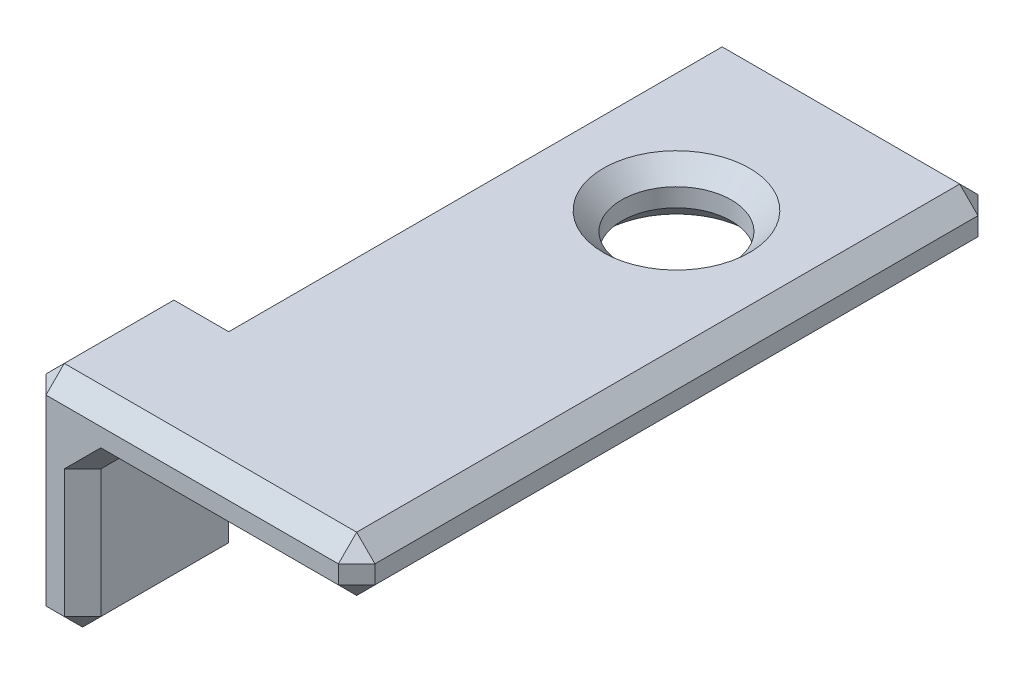
SolidWorks part; units mm, degrees
ref_plane "前视基准面" through (0, 0, 0) normal (0, 0, 1) x (1, 0, 0)
ref_plane "上视基准面" through (0, 0, 0) normal (0, 1, 0) x (1, 0, 0)
ref_plane "右视基准面" through (0, 0, 0) normal (1, 0, 0) x (0, 0, -1)
other "Configuration Table"
sketch "草图1" plane through (0, 0, 0) normal (0, 1, 0) x (1, 0, 0)
  line L0 (7.5, 0) -> (7.5, -20) construction
  line L1 (0, 0) -> (15, 0)
  line L2 (0, 0) -> (0, -20)
  line L3 (0, -20) -> (15, -20)
  line L4 (15, 0) -> (15, -20)
  line L5 (0, -10) -> (15, -10) construction
  circle A0 centre (7.5, -10) radius 3
  point P11 (7.5, -10)
  dimension "D3" = 6
  dimension "D1" = 20
  dimension "D2" = 15
extrude "凸台-拉伸1" add sketch "草图1" along normal blind 3
sketch "草图2" plane through (0, 3, 0) normal (0, 1, 0) x (1, 0, 0)
  line L0 (15, -20) -> (15, 0) construction
  line L1 (0, -20) -> (15, -20)
  line L2 (0, -20) -> (0, -35)
  line L3 (0, -35) -> (15, -35)
  line L4 (15, -20) -> (15, -35)
  dimension "D1" = 15
extrude "凸台-拉伸2" add sketch "草图2" against normal blind 3
sketch "草图4" plane through (0, 0, 0) normal (0, -1, 0) x (1, 0, 0)
  line L1 (0, 35) -> (-3, 35)
  line L2 (0, 35) -> (0, 27)
  line L3 (0, 27) -> (-3, 27)
  line L4 (-3, 35) -> (-3, 27)
  dimension "D1" = 3
  dimension "D2" = 8
extrude "凸台-拉伸3" add sketch "草图4" along normal blind 9 and the other way blind 3
chamfer "倒角1" distance 1 angle 45 20 edges at (7.5, 0, 13) (7.5, 3, 13) (15, 3, 17.5) (7.5, 3, 0) (7.5, 0, 35) (15, 1.5, 35) (6, 3, 35) (0, -4.5, 35) (-1.5, 3, 27) (-3, -3, 27) (-3, 3, 31) (-3, -3, 35) (0, -9, 31) (-1.5, -9, 35) (-3, -9, 31) (0, 3, 13.5) (7.5, 0, 0) (15, 0, 17.5) (0, 1.5, 0) (15, 1.5, 0)
